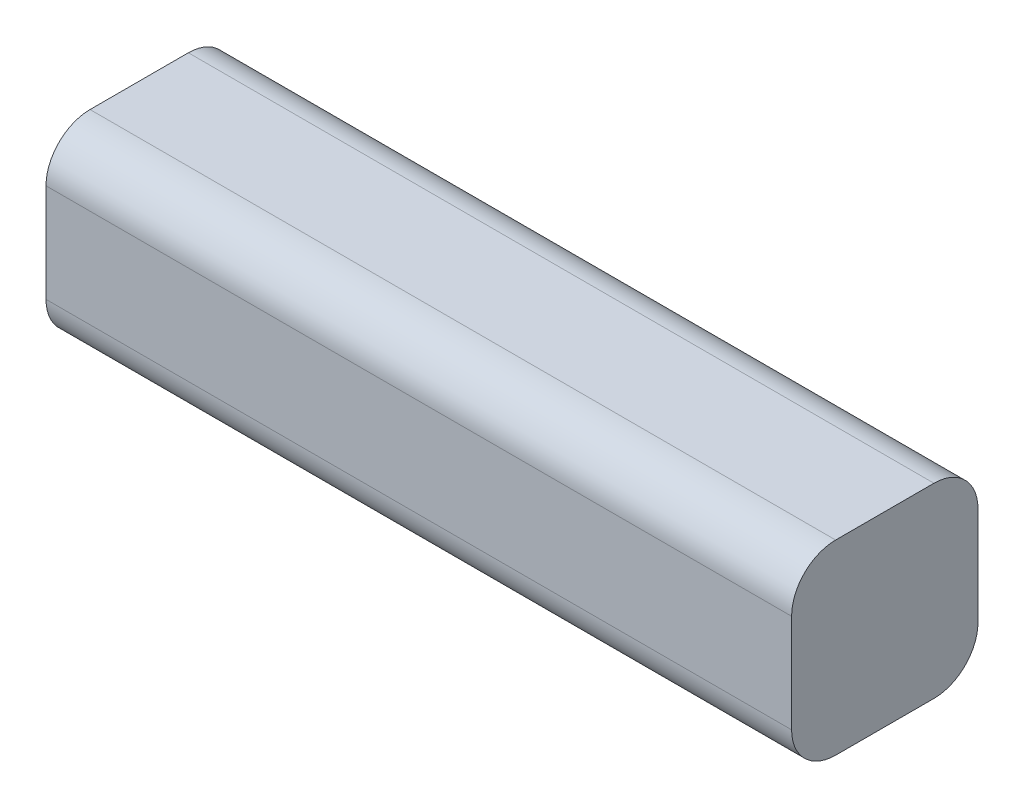
SolidWorks part; units mm, degrees
ref_plane "Front Plane" through (0, 0, 0) normal (0, 0, 1) x (1, 0, 0)
ref_plane "Top Plane" through (0, 0, 0) normal (0, 1, 0) x (1, 0, 0)
ref_plane "Right Plane" through (0, 0, 0) normal (1, 0, 0) x (0, 0, -1)
sketch "Sketch1" plane through (0, 0, 0) normal (0, 1, 0) x (1, 0, 0)
  line L1 (0, 0) -> (152.4, 0)
  line L2 (0, 0) -> (0, 38.1)
  line L3 (0, 38.1) -> (152.4, 38.1)
  line L4 (152.4, 0) -> (152.4, 38.1)
  dimension "D1" = 152.4
  dimension "D2" = 38.1
extrude "Boss-Extrude1" add sketch "Sketch1" along normal blind 38.1
fillet "Fillet1" radius 9 4 edges at (76.2, 38.1, 0) (76.2, 0, -38.1) (76.2, 38.1, -38.1) (76.2, 0, 0)
